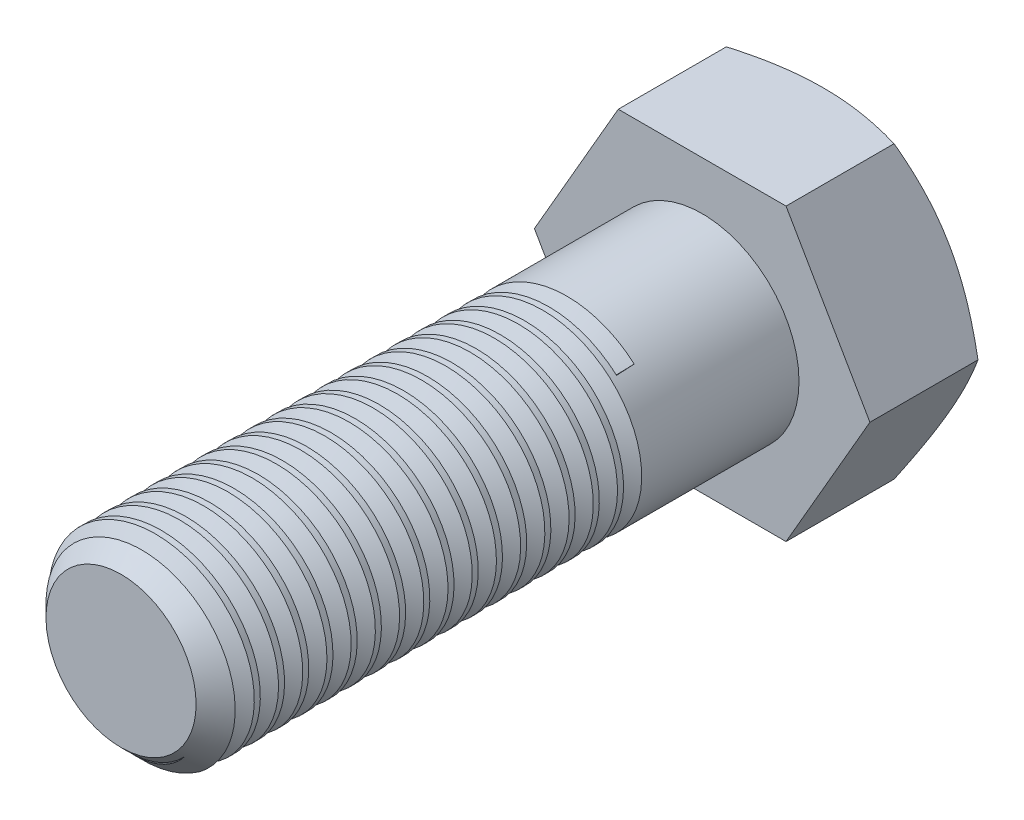
SolidWorks part; units mm, degrees
ref_plane "Front" through (0, 0, 0) normal (0, 0, 1) x (1, 0, 0)
ref_plane "Top" through (0, 0, 0) normal (0, 1, 0) x (1, 0, 0)
ref_plane "Right" through (0, 0, 0) normal (1, 0, 0) x (0, 0, -1)
sketch "Çizim1" plane through (0, 0, 0) normal (0, 0, 1) x (1, 0, 0)
  line L1 (17.3205, 0) -> (8.6603, 15)
  line L2 (8.6603, 15) -> (-8.6603, 15)
  line L3 (-8.6603, 15) -> (-17.3205, 0)
  line L4 (-17.3205, 0) -> (-8.6603, -15)
  line L5 (-8.6603, -15) -> (8.6603, -15)
  line L6 (8.6603, -15) -> (17.3205, 0)
  circle A0 centre (0, 0) radius 15 construction
  dimension "D1" = 30
extrude "Yükseklik-Ekstrüzyon1" add sketch "Çizim1" along normal blind 12.5
sketch "Çizim2" plane through (0, 0, 0) normal (0, 0, -1) x (-1, 0, 0)
  circle A0 centre (0, 0) radius 15
extrude "Kes-Ekstrüzyon1" cut sketch "Çizim2" against normal blind 12.5 draft 60 flip side to cut
sketch "Çizim3" plane through (0, 0, 12.5) normal (0, 0, 1) x (1, 0, 0)
  circle A0 centre (0, 0) radius 10
  dimension "D1" = 20
extrude "Yükseklik-Ekstrüzyon2" add sketch "Çizim3" along normal blind 60
chamfer "Pah1" distance 2.25 angle 45 1 edges at (10, 0, 72.5)
sketch "Çizim4" plane through (0, 0, 72.5) normal (0, 0, 1) x (1, 0, 0)
  circle A0 centre (0, 0) radius 10
curve "Helis/Spiral1" pitch 2.5 height 45 turns 18
ref_plane "Düzlem1" through (7.0711, 7.0711, 72.5) normal (0.7065, -0.7065, -0.0398) x (-0.0281, 0.0281, -0.9992)
sketch "Çizim5" plane through (7.0711, 7.0711, 72.5) normal (0.7065, -0.7065, -0.0398) x (-0.0281, 0.0281, -0.9992)
  line L0 (1.1163, 0.3085) -> (-1.1163, 0.3085)
  line L1 (0, -1.625) -> (1.1163, 0.3085)
  line L3 (-1.1163, 0.3085) -> (0, -1.625)
  line L5 (0, 0.8125) -> (-1.4073, 0.8125) [skipped]
  circle A0 centre (0, 0) radius 0.8125 construction
  dimension "D1" = 1.625
sweep "Kes-Süpür1" cut profiles "Çizim5" path "Helis/Spiral1"
